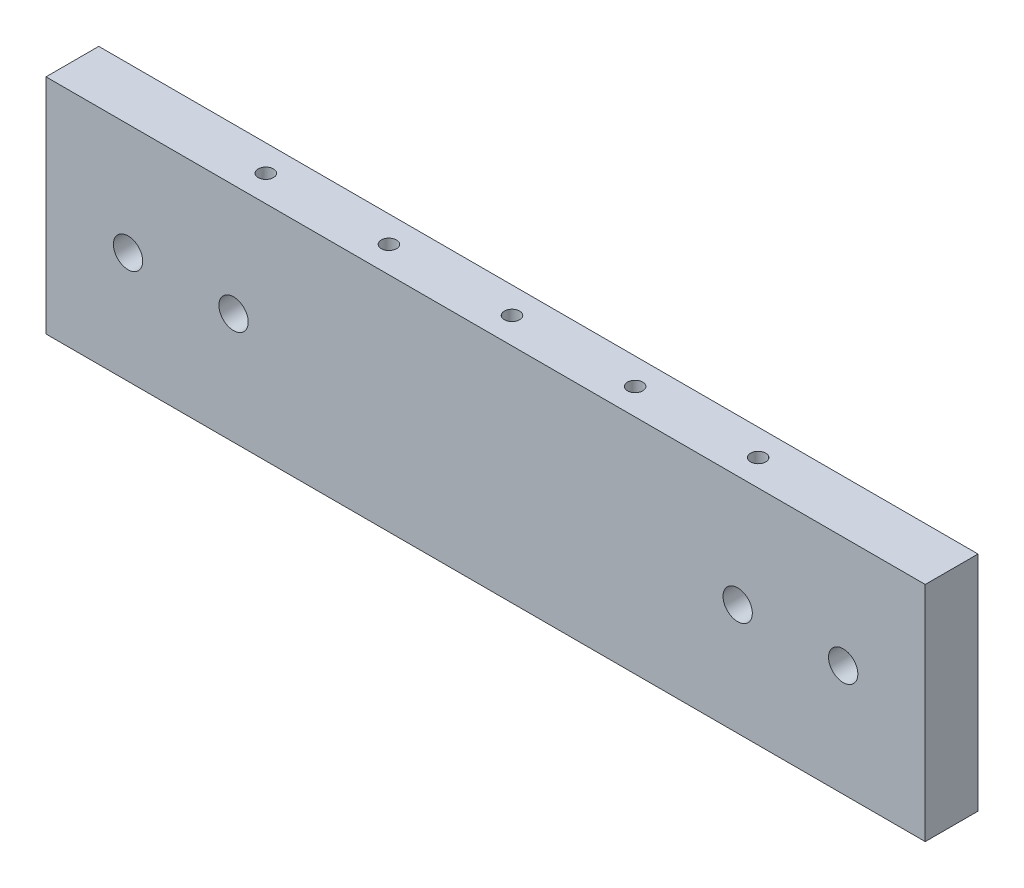
SolidWorks part; units mm, degrees
ref_plane "前基準面" through (0, 0, 0) normal (0, 0, 1) x (1, 0, 0)
ref_plane "上基準面" through (0, 0, 0) normal (0, 1, 0) x (1, 0, 0)
ref_plane "右基準面" through (0, 0, 0) normal (1, 0, 0) x (0, 0, -1)
sketch "草圖1" plane through (0, 0, 0) normal (0, 0, 1) x (1, 0, 0)
  line L1 (-75, 19) -> (75, 19)
  line L2 (-75, 19) -> (-75, -19)
  line L3 (-75, -19) -> (75, -19)
  line L4 (75, 19) -> (75, -19)
  line L5 (-75, 19) -> (75, -19) construction
  line L6 (-75, -19) -> (75, 19) construction
  point P0 (0, 0)
  dimension "D1" = 38
  dimension "D2" = 150
extrude "填料-伸長1" add sketch "草圖1" along normal blind 9
sketch "草圖2" plane through (0, 19, 0) normal (0, 1, 0) x (1, 0, 0)
  line L0 (-75, -9) -> (-75, 0) construction
  circle A0 centre (-42, -4.5) radius 1.3
  point P4 (-75, -4.5)
  dimension "D1" = 2.6
  dimension "D2" = 33
extrude "除料-伸長1" cut sketch "草圖2" against normal blind 8
pattern_linear "直線複製排列1" count 5 spacing 21 along (1, 0, 0) of "除料-伸長1"
mirror "鏡射1" about plane through (0, 0, 0) normal (0, 1, 0) of "除料-伸長1", "直線複製排列1"
sketch "草圖3" plane through (0, 0, 9) normal (0, 0, 1) x (1, 0, 0)
  line L26 (-75, 19) -> (-75, -19) construction
  circle A0 centre (-61, 0) radius 2.5
  circle A1 centre (-43, 0) radius 2.5
  dimension "D6" = 5
  dimension "D1" = 14
  dimension "D8" = 18
extrude "除料-伸長2" cut sketch "草圖3" against normal up to next
mirror "鏡射2" about plane through (0, 0, 0) normal (1, 0, 0) of "除料-伸長2"
